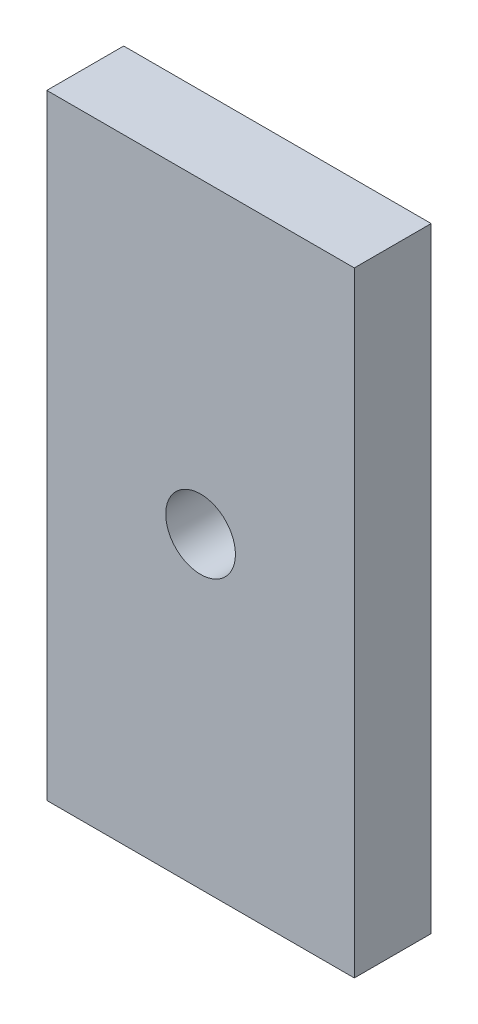
SolidWorks part; units mm, degrees
material "Custom Plastic"
ref_plane "Front Plane" through (0, 0, 0) normal (0, 0, 1) x (1, 0, 0)
ref_plane "Top Plane" through (0, 0, 0) normal (0, 1, 0) x (1, 0, 0)
ref_plane "Right Plane" through (0, 0, 0) normal (1, 0, 0) x (0, 0, -1)
sketch "Sketch2" plane through (0, 0, 0) normal (0, 0, 1) x (1, 0, 0)
  line L5 (-47.7627, 47.7627) -> (47.7627, -47.7627) construction
  line L6 (-47.7627, -47.7627) -> (47.7627, 47.7627) construction
  line L8 (19.05, 38.1) -> (19.05, -38.1)
  line L9 (-19.05, 38.1) -> (-19.05, -38.1)
  line L10 (-19.05, 38.1) -> (19.05, 38.1)
  line L11 (-19.05, -38.1) -> (19.05, -38.1)
  point P0 (0, 0)
  dimension "D1" = 19.05
  dimension "D2" = 19.05
  dimension "D3" = 38.1
  dimension "D4" = 38.1
extrude "Boss-Extrude1" add sketch "Sketch2" along normal blind 9.525
sketch "Sketch3" plane through (0, 0, 9.525) normal (0, 0, 1) x (1, 0, 0)
  line L0 (-19.05, 38.1) -> (-19.05, -38.1)
  line L1 (-19.05, -38.1) -> (19.05, -38.1)
  line L2 (19.05, -38.1) -> (19.05, 38.1)
  line L3 (19.05, 38.1) -> (-19.05, 38.1)
  circle A4 centre (0, 0) radius 4.318
extrude "Cut-Extrude2" cut sketch "Sketch3" against normal blind 12.7 flip side to cut
